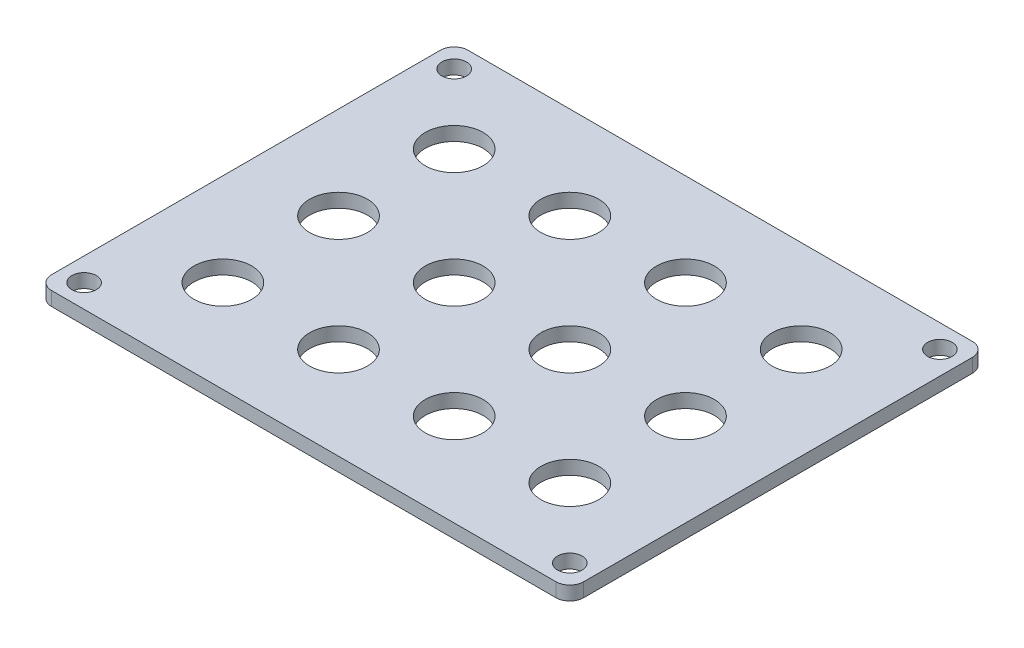
SolidWorks part; units mm, degrees
ref_plane "Front Plane" through (0, 0, 0) normal (0, 0, 1) x (1, 0, 0)
ref_plane "Top Plane" through (0, 0, 0) normal (0, 1, 0) x (1, 0, 0)
ref_plane "Right Plane" through (0, 0, 0) normal (1, 0, 0) x (0, 0, -1)
sketch "Sketch1" plane through (0, 0, 0) normal (0, 1, 0) x (1, 0, 0)
  line L1 (0, 0) -> (115, 0)
  line L2 (0, 0) -> (0, 90)
  line L3 (0, 90) -> (115, 90)
  line L4 (115, 0) -> (115, 90)
  dimension "D1" = 90
  dimension "D2" = 115
extrude "Boss-Extrude1" add sketch "Sketch1" along normal blind 3
sketch "Sketch2" plane through (0, 3, 0) normal (0, 1, 0) x (1, 0, 0)
  line L0 (115, 90) -> (0, 90) construction
  line L1 (0, 90) -> (0, 0) construction
  circle A0 centre (20, 70) radius 6.25
  dimension "D3" = 12.5
  dimension "D1" = 20
  dimension "D2" = 20
extrude "Cut-Extrude1" cut sketch "Sketch2" against normal up to surface (3 mm away) up to face at (57.5, 0, -45)
pattern_linear "LPattern1" count 4 spacing 25 along (1, 0, 0) count 3 spacing 25 along (0, 0, 1) of "Cut-Extrude1"
fillet "Fillet1" radius 3 4 edges at (115, 1.5, -90) (115, 1.5, 0) (0, 1.5, 0) (0, 1.5, -90)
hole_wizard "M5 Clearance Hole1" positions "Sketch3" profile "Sketch4" hole size "M5" standard "ANSI Metric" end condition up to next
sketch "Sketch3" plane through (0, 3, 0) normal (0, 1, 0) x (1, 0, 0)
  line L0 (5, 85) -> (110, 85) construction
  line L1 (110, 85) -> (110, 5) construction
  line L2 (110, 5) -> (5, 5) construction
  line L3 (5, 5) -> (5, 85) construction
  line L5 (0, 87) -> (0, 3) construction
  line L6 (112, 90) -> (3, 90) construction
  line L7 (115, 3) -> (115, 87) construction
  line L8 (3, 0) -> (112, 0) construction
  point P0 (5, 85)
  point P2 (5, 5)
  point P4 (110, 5)
  point P6 (110, 85)
  dimension "D1" = 5
  dimension "D2" = 5
  dimension "D3" = 5
  dimension "D4" = 5
sketch "Sketch4" plane through (5, 3, -85) normal (1, 0, 0) x (0, 0, 1)
  line L0 (0, 0) -> (0, 3)
  line L1 (0, 3) -> (2.65, 3)
  line L2 (2.65, 3) -> (2.65, 0)
  line L5 (2.65, 0) -> (0, 0)
  line L11 (0, -6.35) -> (0, 107.95) construction
  dimension "Thru Hole Dia." = 5.3
  dimension "Thru Hole Depth" = 3
